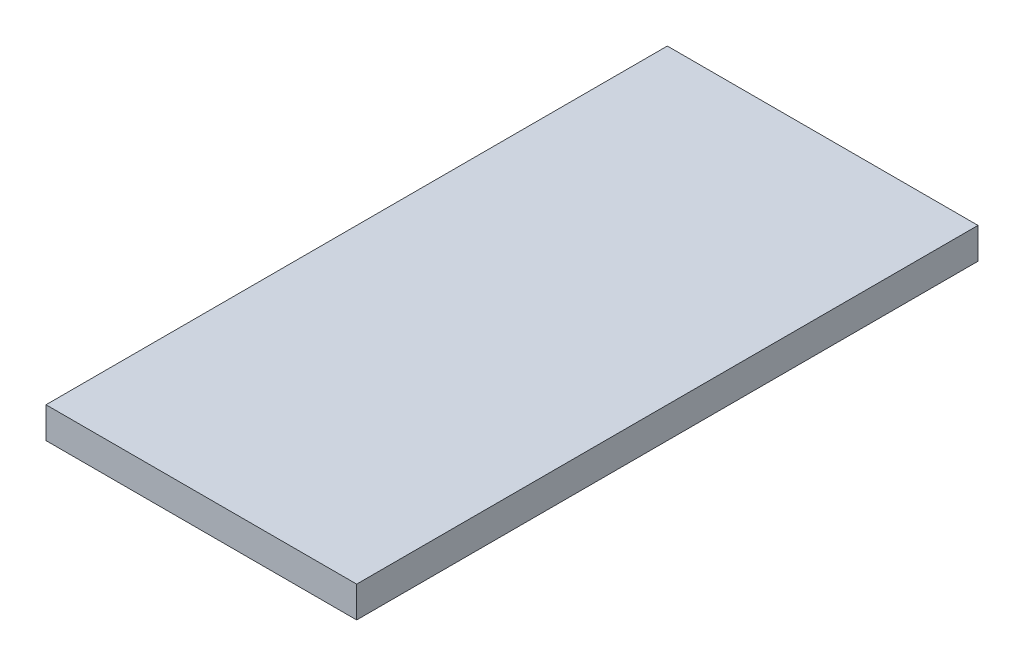
SolidWorks part; units mm, degrees
ref_plane "Front Plane" through (0, 0, 0) normal (0, 0, 1) x (1, 0, 0)
ref_plane "Top Plane" through (0, 0, 0) normal (0, 1, 0) x (1, 0, 0)
ref_plane "Right Plane" through (0, 0, 0) normal (1, 0, 0) x (0, 0, -1)
sketch "Sketch1" plane through (0, 0, 0) normal (0, 1, 0) x (1, 0, 0)
  line L1 (0, 0) -> (5, 0)
  line L2 (0, 0) -> (0, 10)
  line L3 (0, 10) -> (5, 10)
  line L4 (5, 0) -> (5, 10)
  dimension "D1" = 5
  dimension "D2" = 10
extrude "Boss-Extrude1" add sketch "Sketch1" along normal blind 0.5
equation "\"Width\"=5mm"
equation "\"Length\"= 2 * \"Width\""
equation "\"D1@Sketch1\"=\"Width\" "
equation "\"D2@Sketch1\"= \"Length\""
